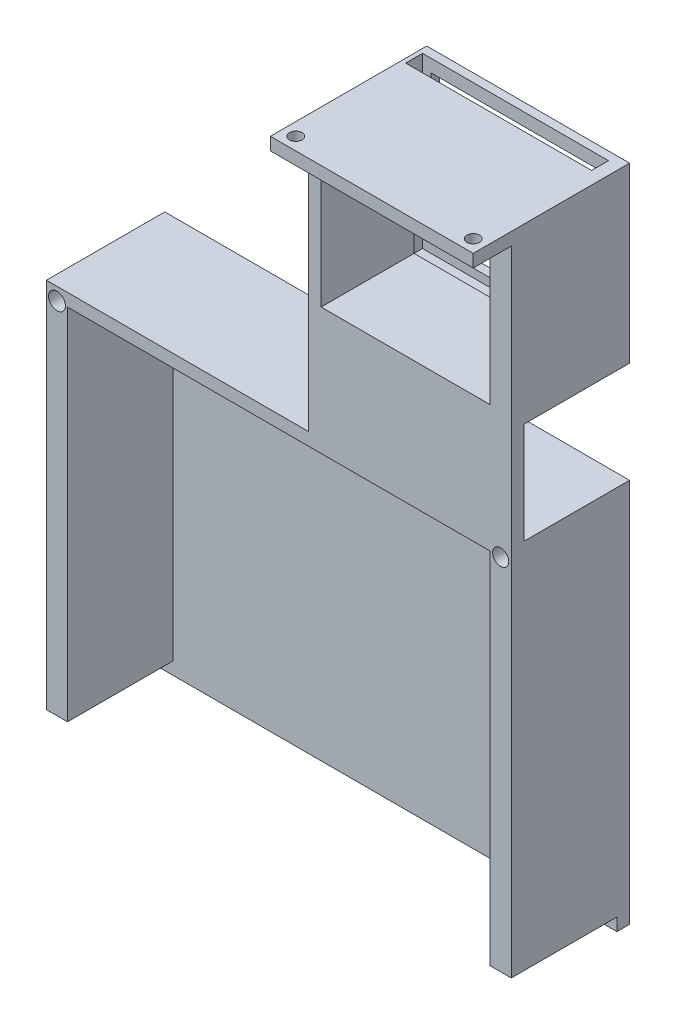
SolidWorks part; units mm, degrees
ref_plane "Přední rovina" through (0, 0, 0) normal (0, 0, 1) x (1, 0, 0)
ref_plane "Horní rovina" through (0, 0, 0) normal (0, 1, 0) x (1, 0, 0)
ref_plane "Pravá rovina" through (0, 0, 0) normal (1, 0, 0) x (0, 0, -1)
sketch "Skica1" plane through (0, 0, 0) normal (0, 0, 1) x (1, 0, 0)
  line L1 (0, 0) -> (40, 0)
  line L2 (0, 0) -> (0, 85)
  line L3 (0, 85) -> (40, 85)
  line L4 (40, 0) -> (40, 85)
  line L5 (0, 85) -> (40, 85)
  line L6 (0, 85) -> (0, 120)
  line L7 (0, 120) -> (40, 120)
  line L8 (40, 85) -> (40, 120)
  line L9 (0, 120) -> (40, 120)
  line L10 (0, 120) -> (0, 150)
  line L11 (0, 150) -> (40, 150)
  line L12 (40, 120) -> (40, 150)
  line L14 (40, 0) -> (40, 85)
  dimension "D1" = 85
  dimension "D2" = 35
  dimension "D3" = 30
  dimension "D4" = 40
extrude "Přidat vysunutím1" add sketch "Skica1" against normal blind 3 contours L1 L4 L3 L2 | L3 L8 L7 L6 | L7 L12 L11 L10
sketch "Skica3" plane through (0, 0, -3) normal (0, 0, -1) x (-1, 0, 0)
  line L0 (0, 0) -> (0, 150) construction
  line L5 (-40, 0) -> (0, 0)
  line L6 (-40, 0) -> (-40, 150)
  line L7 (-40, 150) -> (0, 150)
  line L8 (0, 0) -> (0, 150)
extrude "Vysunout tenkostěnný1" add sketch "Skica3" against normal blind 28 thin
sketch "Skica4" plane through (0, 0, 0) normal (0, 0, 1) x (1, 0, 0)
  line L0 (40, 0) -> (40, 150) construction
  line L1 (0, 0) -> (40, 0)
  line L2 (0, 0) -> (0, 85)
  line L3 (0, 85) -> (40, 85)
  line L4 (40, 0) -> (40, 85)
  line L5 (0, 0) -> (0, 150) construction
  line L6 (0, 85) -> (40, 85)
  line L7 (0, 85) -> (0, 88)
  line L8 (0, 88) -> (40, 88)
  line L9 (40, 85) -> (40, 88)
  line L10 (0, 150) -> (40, 150)
  line L11 (0, 150) -> (0, 115)
  line L12 (0, 115) -> (40, 115)
  line L13 (40, 150) -> (40, 115)
  line L14 (0, 115) -> (40, 115)
  line L15 (0, 115) -> (0, 112)
  line L16 (0, 112) -> (40, 112)
  line L17 (40, 115) -> (40, 112)
  line L18 (43, 153) -> (43, -3) construction
  line L19 (0, 88) -> (40, 88)
  line L21 (0, 112) -> (40, 112)
  line L23 (40, 88) -> (43, 88)
  line L25 (40, 112) -> (43, 112)
  line L26 (43, 88) -> (43, 112)
  line L27 (0, 88) -> (-6.9637, 88)
  line L29 (0, 112) -> (-6.9637, 112)
  line L30 (-6.9637, 88) -> (-6.9637, 112)
  line M20 (40, 0) -> (40, 150)
  line M22 (0, 150) -> (0, 0)
  dimension "D1" = 85
  dimension "D2" = 35
  dimension "D3" = 3
  dimension "D4" = 3
  dimension "D5" = 24
extrude "Odebrat vysunutím2" cut sketch "Skica4" against normal blind 17 and the other way blind 22 contours L16 L8 M22 M20 | L30 L27 L29 M22 | L23 L26 L25 M20
sketch "Skica5" plane through (0, 0, 0) normal (0, 0, 1) x (1, 0, 0)
  line L0 (40, 0) -> (40, 88) construction
  line L1 (0, 112) -> (43, 112)
  line L2 (0, 112) -> (0, 115)
  line L3 (0, 115) -> (43, 115)
  line L4 (43, 112) -> (43, 115)
  line L5 (0, 88) -> (40, 88)
  line L6 (0, 88) -> (0, 85)
  line L7 (0, 85) -> (40, 85)
  line L8 (40, 88) -> (40, 85)
  line L9 (43, 153) -> (43, 112) construction
  dimension "D1" = 3
  dimension "D2" = 3
extrude "Přidat vysunutím2" add sketch "Skica5" along normal blind 25
sketch "Skica6" plane through (0, 0, 25) normal (0, 0, 1) x (1, 0, 0)
  line L1 (0, 88) -> (40, 88)
  line L2 (0, 88) -> (0, 112)
  line L3 (0, 112) -> (40, 112)
  line L4 (40, 88) -> (40, 112)
extrude "Přidat vysunutím3" add sketch "Skica6" against normal blind 3
sketch "Skica7" plane through (0, 0, 0) normal (0, 0, 1) x (1, 0, 0)
  line L0 (40, 115) -> (40, 150) construction
  line L1 (0, 115) -> (40, 115)
  line L2 (0, 115) -> (0, 150)
  line L3 (0, 150) -> (40, 150)
  line L4 (40, 115) -> (40, 150)
extrude "Odebrat vysunutím3" cut sketch "Skica7" against normal through all
sketch "Skica8" plane through (0, 153, 0) normal (0, 1, 0) x (1, 0, 0)
  line L0 (-3, -25) -> (-3, 3) construction
  line L1 (43, 3) -> (-3, 3)
  line L2 (43, 3) -> (43, 1)
  line L3 (43, 1) -> (-3, 1)
  line L4 (-3, 3) -> (-3, 1)
  line L6 (43, 1) -> (-3, 1)
  line L7 (43, 1) -> (43, -3)
  line L8 (43, -3) -> (-3, -3)
  line L9 (-3, 1) -> (-3, -3)
  line L10 (43, -3) -> (42, -3)
  line L11 (43, -3) -> (43, 1)
  line L12 (43, 1) -> (42, 1)
  line L13 (42, -3) -> (42, 1)
  line L14 (-3, -3) -> (-2, -3)
  line L15 (-3, -3) -> (-3, 1)
  line L16 (-3, 1) -> (-2, 1)
  line L17 (-2, -3) -> (-2, 1)
  dimension "D1" = 2
  dimension "D2" = 4
  dimension "D3" = 1
  dimension "D4" = 1
extrude "Odebrat vysunutím4" cut sketch "Skica8" against normal blind 40 contours L17 L8 L13 L6
sketch "Skica13" plane through (0, 0, -3) normal (0, 0, -1) x (-1, 0, 0)
  line L0 (0, 85) -> (-40, 85) construction
  line L1 (0, 0) -> (60, 0)
  line L2 (0, 0) -> (0, 85)
  line L3 (0, 85) -> (60, 85)
  line L4 (60, 0) -> (60, 85)
  dimension "D1" = 60
extrude "Přidat vysunutím7" add sketch "Skica13" against normal blind 3
sketch "Skica14" plane through (0, 0, -3) normal (0, 0, -1) x (-1, 0, 0)
  line L0 (63, 88) -> (63, -3)
  line L1 (60, 85) -> (3, 85)
  line L2 (60, 85) -> (60, 0)
  line L3 (60, 0) -> (3, 0)
  line L4 (3, 85) -> (3, 0)
  line L5 (63, -3) -> (0, -3)
  line L6 (0, 88) -> (0, -3)
  line L7 (63, 88) -> (0, 88)
  dimension "D1" = 3
extrude "Přidat vysunutím8" add sketch "Skica14" against normal up to surface (28 mm away)
sketch "Skica15" plane through (0, 0, 25) normal (0, 0, 1) x (1, 0, 0)
  line L1 (-3, 85) -> (0, 85)
  line L2 (-3, 85) -> (-3, 0)
  line L3 (-3, 0) -> (0, 0)
  line L4 (0, 85) -> (0, 0)
extrude "Odebrat vysunutím6" cut sketch "Skica15" against normal up to surface (25 mm away) up to face at (-31.5, 42.5, 0)
sketch "Skica16" plane through (0, 0, 25) normal (0, 0, 1) x (1, 0, 0)
  line L1 (43, 153) -> (-3, 153)
  line L2 (43, 153) -> (43, 150)
  line L3 (43, 150) -> (-3, 150)
  line L4 (-3, 153) -> (-3, 150)
extrude "Přidat vysunutím9" add sketch "Skica16" along normal up to surface (9 mm away)
sketch "Skica17" plane through (0, 0, 34) normal (0, 0, 1) x (1, 0, 0)
  line L1 (45, -3) -> (-65, -3)
  line L2 (45, -3) -> (45, 0)
  line L3 (45, 0) -> (-65, 0)
  line L4 (-65, -3) -> (-65, 0)
  line L5 (-65, 88) -> (-65, -3) construction
  dimension "D1" = 3
extrude "Odebrat vysunutím7" cut sketch "Skica17" against normal blind 34
ref_plane "Rovina1" through (40, 150, 25) normal (0, 0, -1) x (-1, 0, 0)
sketch "Skica21" plane through (-63, 0, 0) normal (-1, 0, 0) x (0, 0, 1)
  line L0 (-3, -3) -> (-3, 88) construction
  line L1 (25, 88) -> (-3, 88)
  line L2 (25, 88) -> (25, 0)
  line L3 (25, 0) -> (-3, 0)
  line L4 (-3, 88) -> (-3, 0)
  line L5 (0, -3) -> (-3, -3) construction
  line L6 (-3, 0) -> (0, 0)
  line L7 (-3, 0) -> (-3, -3)
  line L8 (-3, -3) -> (0, -3)
  line L9 (0, 0) -> (0, -3)
  line L10 (0, -3) -> (0, 0) construction
  line M1 (0, 0) -> (25, 0)
  line M2 (25, 0) -> (25, 88)
  line M3 (25, 88) -> (-3, 88)
  line M4 (-3, 88) -> (-3, -3)
extrude "Přidat vysunutím10" add sketch "Skica21" along normal blind 2 contours L3 M1 M2 M3 M4 | L7 L8 L9 L6
sketch "Skica22" plane through (43, 0, 0) normal (1, 0, 0) x (0, 0, -1)
  line L0 (-34, 153) -> (3, 153) construction
  line L1 (-25, 0) -> (0, 0)
  line L2 (-25, 0) -> (-25, 88)
  line L3 (-22, 88) -> (3, 88)
  line L4 (3, 0) -> (3, 88)
  line L5 (3, -3) -> (0, -3)
  line L6 (3, -3) -> (3, 0)
  line L8 (0, -3) -> (0, 0)
  line L10 (-25, 88) -> (-25, 112)
  line L12 (-22, 88) -> (-22, 112)
  line L13 (3, 112) -> (-22, 112)
  line L14 (3, 112) -> (3, 153)
  line L15 (3, 153) -> (-25, 153)
  line L16 (-25, 112) -> (-25, 150)
  line L18 (-25, 153) -> (-34, 153)
  line L20 (-25, 150) -> (-34, 150)
  line L21 (-34, 153) -> (-34, 150)
extrude "Přidat vysunutím11" add sketch "Skica22" along normal blind 2
sketch "Skica23" plane through (0, 0, 0) normal (0, -1, 0) x (1, 0, 0)
  line L0 (-65, 25) -> (-65, 0) construction
  line L1 (-65, 25) -> (-60, 25) construction
  line L3 (-65, 0) -> (45, 0) construction
  line L4 (45, 25) -> (45, 0) construction
  circle A0 centre (42.5, 22.5) radius 2
  circle A1 centre (42.5, 2.5) radius 2
  circle A2 centre (-62.5, 2.5) radius 2
  circle A3 centre (-62.5, 22.5) radius 2
  dimension "D1" = 4
  dimension "D2" = 2.5
  dimension "D3" = 2.5
  dimension "D4" = 2.5
  dimension "D5" = 2.5
extrude "Odebrat vysunutím10" cut sketch "Skica23" against normal blind 5
sketch "Skica19" plane through (0, 153, 0) normal (0, 1, 0) x (1, 0, 0)
  circle A0 centre (42, -31) radius 1.5
  circle A1 centre (42, -31) radius 2 construction
  circle A2 centre (0, -31) radius 1.5
  circle A4 centre (0, -31) radius 2 construction
  dimension "D1" = 3
extrude "Odebrat vysunutím8" cut sketch "Skica19" against normal through all both and the other way through all
sketch "Skica24" plane through (0, 0, 25) normal (0, 0, 1) x (1, 0, 0)
  line L0 (-65, 0) -> (-65, 88) construction
  line L1 (-3, 88) -> (-65, 88) construction
  line L2 (45, 150) -> (45, 0) construction
  circle A0 centre (-62.5, 85) radius 2
  circle A1 centre (42.5, 85) radius 1.9104
  dimension "D1" = 4
  dimension "D2" = 2.5
  dimension "D3" = 3
  dimension "D4" = 2.5
extrude "Odebrat vysunutím11" cut sketch "Skica24" against normal blind 5
